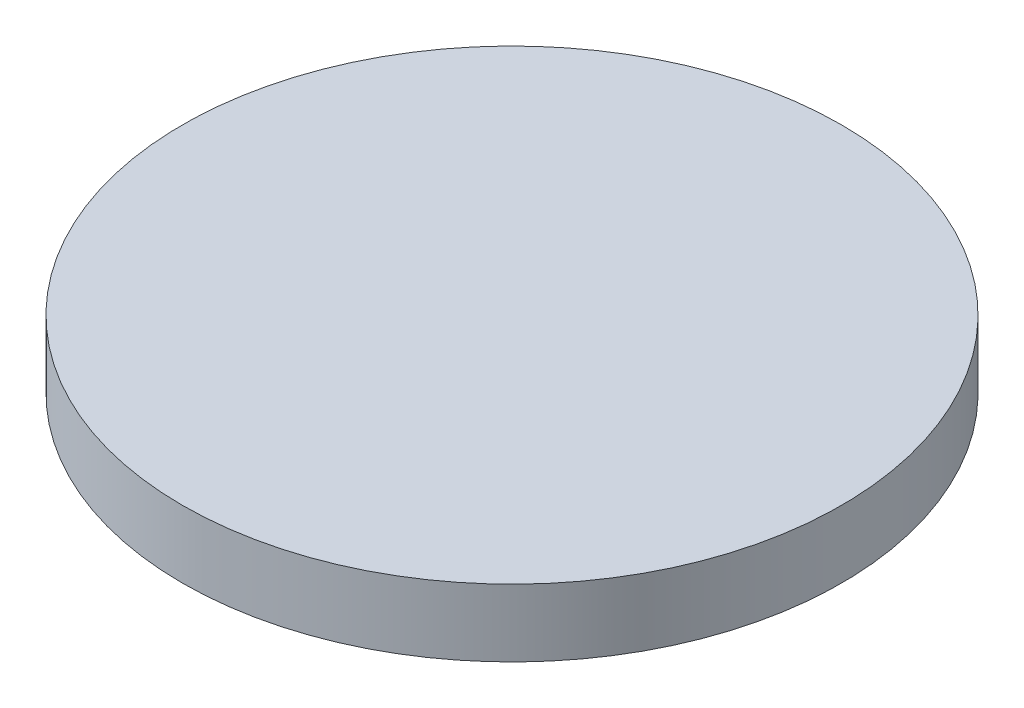
SolidWorks part; units mm, degrees
ref_plane "前视基准面" through (0, 0, 0) normal (0, 0, 1) x (1, 0, 0)
ref_plane "上视基准面" through (0, 0, 0) normal (0, 1, 0) x (1, 0, 0)
ref_plane "右视基准面" through (0, 0, 0) normal (1, 0, 0) x (0, 0, -1)
sketch "草图1" plane through (0, 0, 0) normal (0, 1, 0) x (1, 0, 0)
  circle A0 centre (0, 0) radius 89.215
  dimension "D1" = 178.43
extrude "凸台-拉伸1" add sketch "草图1" along normal blind 18.24
